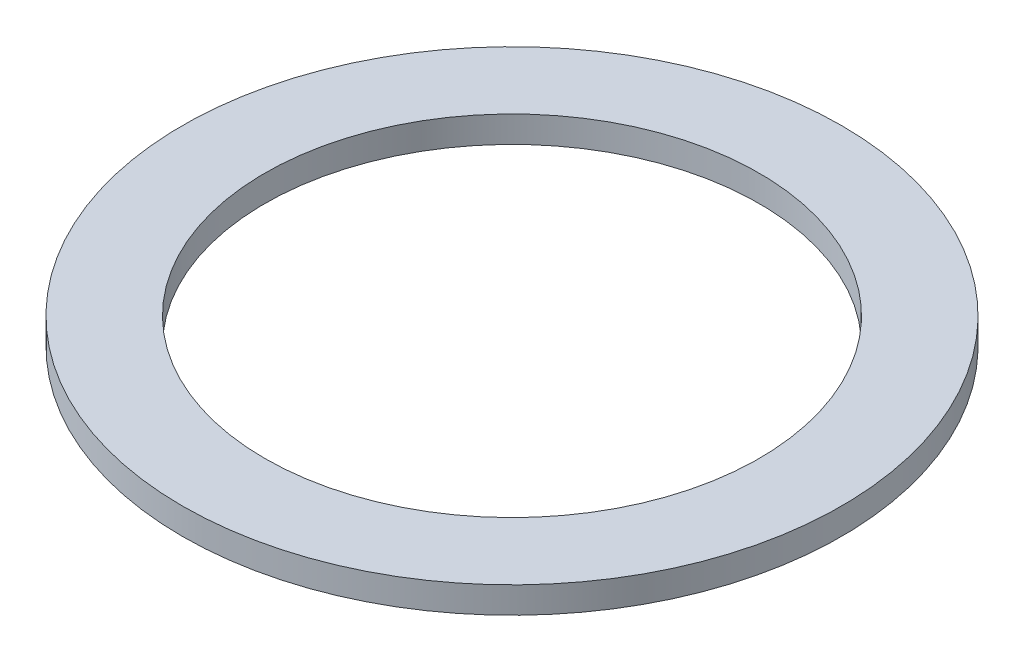
SolidWorks part; units mm, degrees
ref_plane "Front Plane" through (0, 0, 0) normal (0, 0, 1) x (1, 0, 0)
ref_plane "Top Plane" through (0, 0, 0) normal (0, 1, 0) x (1, 0, 0)
ref_plane "Right Plane" through (0, 0, 0) normal (1, 0, 0) x (0, 0, -1)
sketch "Sketch1" plane through (0, 0, 0) normal (0, 1, 0) x (1, 0, 0)
  circle A0 centre (0, 0) radius 37.5
  circle A1 centre (0, 0) radius 50
  dimension "D1" = 75
  dimension "D2" = 100
extrude "Boss-Extrude1" add sketch "Sketch1" along normal blind 4
